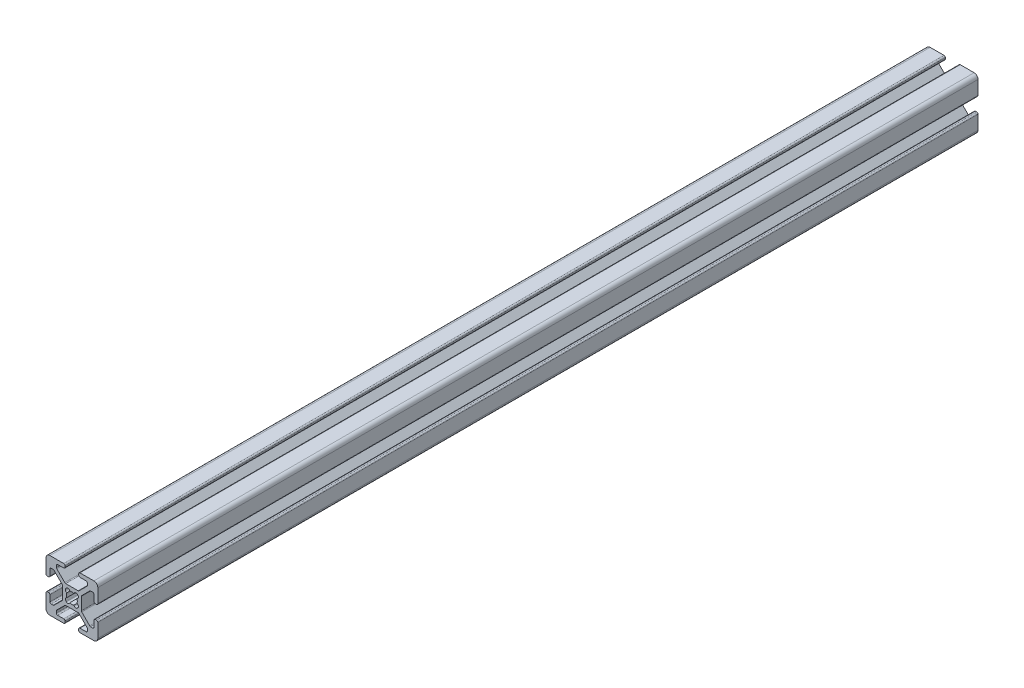
SolidWorks part; units mm, degrees
material "3.3537 (EN-AW 3535)"
ref_plane "Front Plane" through (0, 0, 0) normal (0, 0, 1) x (1, 0, 0)
ref_plane "Top Plane" through (0, 0, 0) normal (0, 1, 0) x (1, 0, 0)
ref_plane "Right Plane" through (0, 0, 0) normal (1, 0, 0) x (0, 0, -1)
sketch "Sketch1" plane through (0, 0, 0) normal (0, 0, 1) x (1, 0, 0)
  line L0 (-5.0323, -0.3411) -> (-5.5163, -0.3411)
  line L1 (-6.0243, 0.1669) -> (-6.0243, 2.5159)
  line L2 (-4.5243, 0.1669) -> (-4.5243, 5.5289)
  line L3 (-10.8693, -5.355) -> (-10.8693, -0.5871)
  line L4 (-7.2582, 3.0239) -> (-6.5323, 3.0239)
  line L5 (-7.6174, 2.8752) -> (-10.7205, -0.2279)
  line L6 (-5.0323, -5.6011) -> (-5.5163, -5.6011)
  line L7 (-4.5243, -6.1091) -> (-4.5243, -11.4711)
  line L8 (-6.0243, -6.1091) -> (-6.0243, -8.4581)
  line L9 (-7.2582, -8.9661) -> (-6.5323, -8.9661)
  line L10 (-7.6174, -8.8173) -> (-10.7205, -5.7142)
  line L11 (-12.3994, -5.2756) -> (-12.2198, -5.096)
  line L12 (-17.1543, 6.5209) -> (-17.1543, 6.0369)
  line L13 (-17.6623, 7.0289) -> (-23.0243, 7.0289)
  line L14 (-17.6623, 5.5289) -> (-20.0113, 5.5289)
  line L15 (-12.1404, 0.6839) -> (-16.9082, 0.6839)
  line L16 (-20.5193, 4.295) -> (-20.5193, 5.0209)
  line L17 (-20.3705, 3.9358) -> (-17.2674, 0.8327)
  line L18 (-11.8943, 6.5209) -> (-11.8943, 6.0369)
  line L19 (-11.3863, 7.0289) -> (-6.0243, 7.0289)
  line L20 (-11.3863, 5.5289) -> (-9.0373, 5.5289)
  line L21 (-8.5293, 4.295) -> (-8.5293, 5.0209)
  line L22 (-8.6781, 3.9358) -> (-11.7812, 0.8327)
  line L23 (-12.2198, -0.8462) -> (-12.3994, -0.6666)
  line L24 (-24.0163, -5.6011) -> (-23.5323, -5.6011)
  line L25 (-24.5243, -6.1091) -> (-24.5243, -11.4711)
  line L26 (-23.0243, -6.1091) -> (-23.0243, -8.4581)
  line L27 (-18.1793, -0.5871) -> (-18.1793, -5.355)
  line L28 (-21.7904, -8.9661) -> (-22.5163, -8.9661)
  line L29 (-21.4312, -8.8173) -> (-18.3281, -5.7142)
  line L30 (-24.0163, -0.3411) -> (-23.5323, -0.3411)
  line L31 (-24.5243, 0.1669) -> (-24.5243, 5.5289)
  line L32 (-23.0243, 0.1669) -> (-23.0243, 2.5159)
  line L33 (-21.7904, 3.0239) -> (-22.5163, 3.0239)
  line L34 (-21.4312, 2.8752) -> (-18.3281, -0.2279)
  line L35 (-16.6492, -0.6666) -> (-16.8288, -0.8462)
  line L36 (-11.8943, -12.4631) -> (-11.8943, -11.9791)
  line L37 (-11.3863, -12.9711) -> (-6.0243, -12.9711)
  line L38 (-11.3863, -11.4711) -> (-9.0373, -11.4711)
  line L39 (-16.9082, -6.6261) -> (-12.1404, -6.6261)
  line L40 (-8.5293, -10.2371) -> (-8.5293, -10.9631)
  line L41 (-8.6781, -9.8779) -> (-11.7812, -6.7748)
  line L42 (-17.1543, -12.4631) -> (-17.1543, -11.9791)
  line L43 (-17.6623, -12.9711) -> (-23.0243, -12.9711)
  line L44 (-17.6623, -11.4711) -> (-20.0113, -11.4711)
  line L45 (-20.5193, -10.2371) -> (-20.5193, -10.9631)
  line L46 (-20.3705, -9.8779) -> (-17.2674, -6.7748)
  line L47 (-16.8288, -5.096) -> (-16.6492, -5.2756)
  arc A0 (-15.3283, -4.9062) -> (-13.7203, -4.9062) centre (-14.5243, -2.9711) ccw
  arc A1 (-6.0243, 2.5159) -> (-6.5323, 3.0239) centre (-6.5323, 2.5159) ccw
  arc A2 (-7.2582, 3.0239) -> (-7.6174, 2.8752) centre (-7.2582, 2.5159) ccw
  arc A3 (-10.7205, -0.2279) -> (-10.8693, -0.5871) centre (-10.3613, -0.5871) ccw
  arc A4 (-10.8693, -5.355) -> (-10.7205, -5.7142) centre (-10.3613, -5.355) ccw
  arc A5 (-7.6174, -8.8173) -> (-7.2582, -8.9661) centre (-7.2582, -8.4581) ccw
  arc A6 (-6.5323, -8.9661) -> (-6.0243, -8.4581) centre (-6.5323, -8.4581) ccw
  arc A7 (-5.5163, -5.6011) -> (-6.0243, -6.1091) centre (-5.5163, -6.1091) ccw
  arc A8 (-4.5243, -6.1091) -> (-5.0323, -5.6011) centre (-5.0323, -6.1091) ccw
  arc A9 (-5.0323, -0.3411) -> (-4.5243, 0.1669) centre (-5.0323, 0.1669) ccw
  arc A10 (-6.0243, 0.1669) -> (-5.5163, -0.3411) centre (-5.5163, 0.1669) ccw
  arc A11 (-13.7203, -4.9062) -> (-12.3994, -5.2756) centre (-12.9559, -4.7191) ccw
  arc A12 (-12.2198, -5.096) -> (-12.5892, -3.775) centre (-12.7763, -4.5395) ccw
  arc A13 (-17.1543, 6.5209) -> (-17.6623, 7.0289) centre (-17.6623, 6.5209) ccw
  arc A14 (-17.6623, 5.5289) -> (-17.1543, 6.0369) centre (-17.6623, 6.0369) ccw
  arc A15 (-12.5892, -3.775) -> (-12.5892, -2.1671) centre (-14.5243, -2.9711) ccw
  arc A16 (-17.2674, 0.8327) -> (-16.9082, 0.6839) centre (-16.9082, 1.1919) ccw
  arc A17 (-20.0113, 5.5289) -> (-20.5193, 5.0209) centre (-20.0113, 5.0209) ccw
  arc A18 (-20.5193, 4.295) -> (-20.3705, 3.9358) centre (-20.0113, 4.295) ccw
  arc A19 (-11.8943, 6.0369) -> (-11.3863, 5.5289) centre (-11.3863, 6.0369) ccw
  arc A20 (-11.3863, 7.0289) -> (-11.8943, 6.5209) centre (-11.3863, 6.5209) ccw
  arc A21 (-8.5293, 5.0209) -> (-9.0373, 5.5289) centre (-9.0373, 5.0209) ccw
  arc A22 (-8.6781, 3.9358) -> (-8.5293, 4.295) centre (-9.0373, 4.295) ccw
  arc A23 (-12.1404, 0.6839) -> (-11.7812, 0.8327) centre (-12.1404, 1.1919) ccw
  arc A24 (-12.5892, -2.1671) -> (-12.2198, -0.8462) centre (-12.7763, -1.4027) ccw
  arc A25 (-12.3994, -0.6666) -> (-13.7203, -1.0359) centre (-12.9559, -1.223) ccw
  arc A26 (-24.0163, -5.6011) -> (-24.5243, -6.1091) centre (-24.0163, -6.1091) ccw
  arc A27 (-23.0243, -6.1091) -> (-23.5323, -5.6011) centre (-23.5323, -6.1091) ccw
  arc A28 (-13.7203, -1.0359) -> (-15.3283, -1.0359) centre (-14.5243, -2.9711) ccw
  arc A29 (-18.3281, -5.7142) -> (-18.1793, -5.355) centre (-18.6873, -5.355) ccw
  arc A30 (-23.0243, -8.4581) -> (-22.5163, -8.9661) centre (-22.5163, -8.4581) ccw
  arc A31 (-21.7904, -8.9661) -> (-21.4312, -8.8173) centre (-21.7904, -8.4581) ccw
  arc A32 (-23.5323, -0.3411) -> (-23.0243, 0.1669) centre (-23.5323, 0.1669) ccw
  arc A33 (-24.5243, 0.1669) -> (-24.0163, -0.3411) centre (-24.0163, 0.1669) ccw
  arc A34 (-22.5163, 3.0239) -> (-23.0243, 2.5159) centre (-22.5163, 2.5159) ccw
  arc A35 (-21.4312, 2.8752) -> (-21.7904, 3.0239) centre (-21.7904, 2.5159) ccw
  arc A36 (-18.1793, -0.5871) -> (-18.3281, -0.2279) centre (-18.6873, -0.5871) ccw
  arc A37 (-15.3283, -1.0359) -> (-16.6492, -0.6666) centre (-16.0927, -1.223) ccw
  arc A38 (-16.8288, -0.8462) -> (-16.4594, -2.1671) centre (-16.2723, -1.4027) ccw
  arc A39 (-11.8943, -12.4631) -> (-11.3863, -12.9711) centre (-11.3863, -12.4631) ccw
  arc A40 (-11.3863, -11.4711) -> (-11.8943, -11.9791) centre (-11.3863, -11.9791) ccw
  arc A41 (-16.4594, -2.1671) -> (-16.4594, -3.775) centre (-14.5243, -2.9711) ccw
  arc A42 (-11.7812, -6.7748) -> (-12.1404, -6.6261) centre (-12.1404, -7.1341) ccw
  arc A43 (-9.0373, -11.4711) -> (-8.5293, -10.9631) centre (-9.0373, -10.9631) ccw
  arc A44 (-8.5293, -10.2371) -> (-8.6781, -9.8779) centre (-9.0373, -10.2371) ccw
  arc A45 (-17.1543, -11.9791) -> (-17.6623, -11.4711) centre (-17.6623, -11.9791) ccw
  arc A46 (-17.6623, -12.9711) -> (-17.1543, -12.4631) centre (-17.6623, -12.4631) ccw
  arc A47 (-20.5193, -10.9631) -> (-20.0113, -11.4711) centre (-20.0113, -10.9631) ccw
  arc A48 (-20.3705, -9.8779) -> (-20.5193, -10.2371) centre (-20.0113, -10.2371) ccw
  arc A49 (-16.9082, -6.6261) -> (-17.2674, -6.7748) centre (-16.9082, -7.1341) ccw
  arc A50 (-16.4594, -3.775) -> (-16.8288, -5.096) centre (-16.2723, -4.5395) ccw
  arc A51 (-16.6492, -5.2756) -> (-15.3283, -4.9062) centre (-16.0927, -4.7191) ccw
  arc A52 (-4.5243, 5.5289) -> (-6.0243, 7.0289) centre (-6.0243, 5.5289) ccw
  arc A53 (-6.0243, -12.9711) -> (-4.5243, -11.4711) centre (-6.0243, -11.4711) ccw
  arc A54 (-24.5243, -11.4711) -> (-23.0243, -12.9711) centre (-23.0243, -11.4711) ccw
  arc A55 (-23.0243, 7.0289) -> (-24.5243, 5.5289) centre (-23.0243, 5.5289) ccw
extrude "Extrude1" add sketch "Sketch1" along normal blind 340
